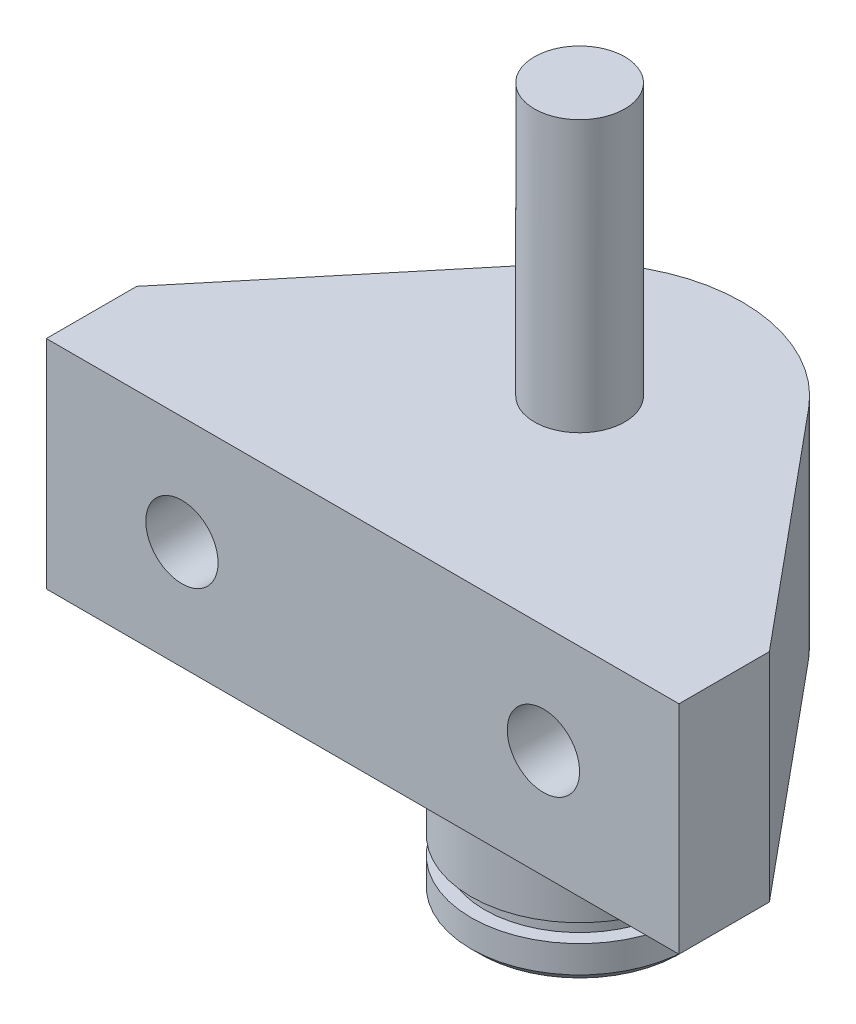
SolidWorks part; units mm, degrees
ref_plane "前视基准面" through (0, 0, 0) normal (0, 0, 1) x (1, 0, 0)
ref_plane "上视基准面" through (0, 0, 0) normal (0, 1, 0) x (1, 0, 0)
ref_plane "右视基准面" through (0, 0, 0) normal (1, 0, 0) x (0, 0, -1)
sketch "草图1" plane through (0, 0, 0) normal (0, 1, 0) x (1, 0, 0)
  line L0 (-40.2621, 0) -> (42.8359, 0) construction
  line L1 (0, 27.1172) -> (0, -30.0587) construction
  line L2 (-17.5, 6.0977) -> (-6.927, 18.8437)
  line L4 (17.5, 6.0977) -> (17.5, 1.0977)
  line L5 (17.5, 1.0977) -> (-17.5, 1.0977)
  line L6 (-17.5, 6.0977) -> (-17.5, 1.0977)
  line L7 (17.5, 6.0977) -> (6.927, 18.8437)
  arc A0 (-6.927, 18.8437) -> (6.927, 18.8437) centre (0, 13.0977) cw
  dimension "D3" = 9
  dimension "D1" = 35
  dimension "D2" = 5
  dimension "D4" = 12
extrude "凸台-拉伸1" add sketch "草图1" along normal blind 12
sketch "草图2" plane through (0, 0, 0) normal (0, 1, 0) x (1, 0, 0)
  line L0 (0, 25.9132) -> (0, -2.6702) construction
  circle A0 centre (0, 13.0977) radius 6
  arc A1 (6.927, 18.8437) -> (-6.927, 18.8437) centre (0, 13.0977) ccw construction
extrude "凸台-拉伸2" add sketch "草图2" against normal blind 9
ref_plane "基准面2" through (0, -9, 0) normal (0, -1, 0) x (-1, 0, 0)
sketch "草图3" plane through (0, -9, 0) normal (0, -1, 0) x (-1, 0, 0)
  line L0 (-16.966, 13.0977) -> (18.1107, 13.0977) construction
  line L1 (0, 24.7208) -> (0, -1.9342) construction
  circle A0 centre (0, 13.0977) radius 5.25
  dimension "D1" = 10.5
extrude "凸台-拉伸3" add sketch "草图3" along normal blind 1
ref_plane "基准面3" through (0, -10, 0) normal (0, -1, 0) x (-1, 0, 0)
sketch "草图4" plane through (0, -10, 0) normal (0, -1, 0) x (-1, 0, 0)
  line L0 (0, 3.871) -> (0, 23.7805) construction
  line L1 (5.25, 13.0977) -> (17.7836, 13.0977) construction
  circle A2 centre (0, 13.0977) radius 6
extrude "凸台-拉伸4" add sketch "草图4" along normal blind 2
chamfer "倒角1" distance 0.5 angle 45 1 edges at (0, -12, -19.0977)
ref_plane "基准面4" through (0, 0, -1.0977) normal (0, 0, 1) x (1, 0, 0)
sketch "草图5" plane through (0, 0, -1.0977) normal (0, 0, 1) x (1, 0, 0)
  line L0 (0, 19.1191) -> (0, -7.9608) construction
  line L1 (1.1746, 6) -> (-25.0031, 6) construction
  line L2 (17.5, 12) -> (17.5, 0) construction
  circle A0 centre (-10, 6) radius 2
  circle A1 centre (10, 6) radius 2
  point P11 (17.5, 6)
  dimension "D1" = 20
extrude "切除-拉伸1" cut sketch "草图5" against normal blind 5
cosmetic thread "装饰螺纹线1" parameters "D2"=12
cosmetic thread "装饰螺纹线2" parameters "D2"=12
ref_plane "基准面5" through (0, 12, 0) normal (0, 1, 0) x (1, 0, 0)
sketch "草图6" plane through (0, 12, 0) normal (0, 1, 0) x (1, 0, 0)
  circle A0 centre (0, 13.0977) radius 2.5
  arc A1 (6.927, 18.8437) -> (-6.927, 18.8437) centre (0, 13.0977) ccw construction
  point P2 (0, 0)
extrude "凸台-拉伸5" add sketch "草图6" along normal blind 15
